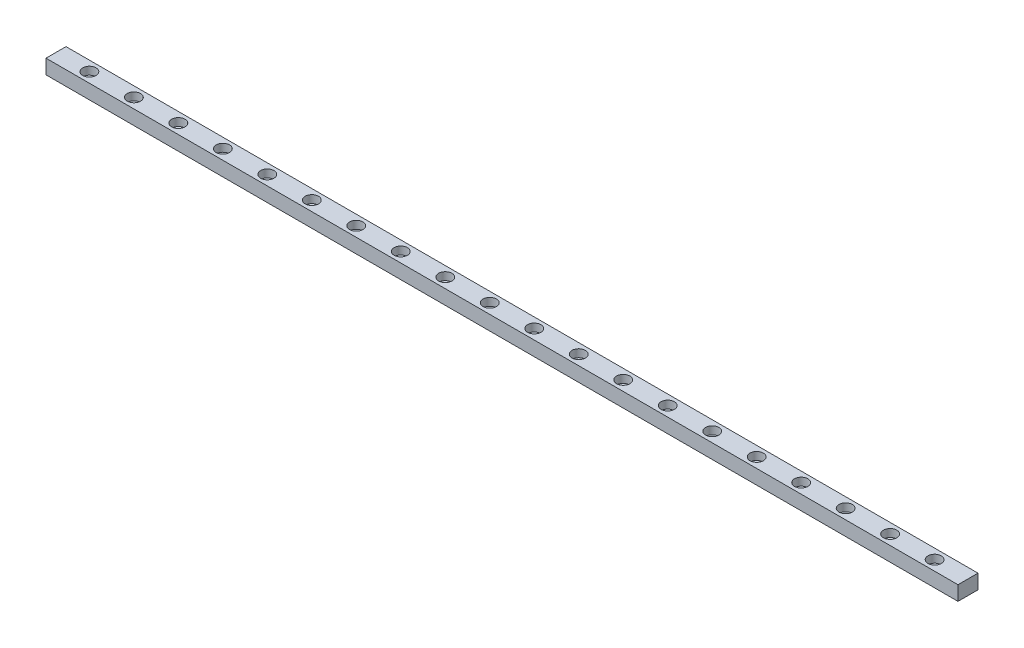
SolidWorks part; units mm, degrees
material "铸造碳钢"
ref_plane "前视基准面" through (0, 0, 0) normal (0, 0, 1) x (1, 0, 0)
ref_plane "上视基准面" through (0, 0, 0) normal (0, 1, 0) x (1, 0, 0)
ref_plane "右视基准面" through (0, 0, 0) normal (1, 0, 0) x (0, 0, -1)
sketch "草图2" plane through (0, 0, 0) normal (1, 0, 0) x (0, 0, -1)
  line L1 (-4.5, 3.25) -> (4.5, 3.25)
  line L2 (-4.5, 3.25) -> (-4.5, -3.25)
  line L3 (-4.5, -3.25) -> (4.5, -3.25)
  line L4 (4.5, 3.25) -> (4.5, -3.25)
  line L5 (-4.5, 3.25) -> (4.5, -3.25) construction
  line L6 (-4.5, -3.25) -> (4.5, 3.25) construction
  point P0 (0, 0)
  dimension "D1" = 9
  dimension "D2" = 6.5
extrude "凸台-拉伸1" add sketch "草图2" along normal blind 410
sketch "草图3" plane through (0, 3.25, 0) normal (0, 1, 0) x (1, 0, 0)
  line L0 (0, 0) -> (410, 0) construction
  line L1 (410, 4.5) -> (410, -4.5) construction
  line L2 (0, 4.5) -> (0, -4.5) construction
  circle A0 centre (15, 0) radius 3
  circle A1 centre (35, 0) radius 3
  circle A2 centre (55, 0) radius 3
  circle A3 centre (75, 0) radius 3
  circle A4 centre (95, 0) radius 3
  circle A5 centre (115, 0) radius 3
  circle A6 centre (135, 0) radius 3
  circle A7 centre (155, 0) radius 3
  circle A8 centre (175, 0) radius 3
  circle A9 centre (195, 0) radius 3
  circle A10 centre (215, 0) radius 3
  circle A11 centre (235, 0) radius 3
  circle A12 centre (255, 0) radius 3
  circle A13 centre (275, 0) radius 3
  circle A14 centre (295, 0) radius 3
  circle A15 centre (315, 0) radius 3
  circle A16 centre (335, 0) radius 3
  circle A17 centre (355, 0) radius 3
  circle A18 centre (375, 0) radius 3
  circle A19 centre (395, 0) radius 3
  dimension "D1" = 15
  dimension "D2" = 6
  dimension "D4" = 20
  dimension "D3" = 20
extrude "切除-拉伸1" cut sketch "草图3" against normal blind 3.5
sketch "草图4" plane through (0, 3.25, 0) normal (0, 1, 0) x (1, 0, 0)
  line L0 (0, 0) -> (90, 0) construction
  line L1 (0, 4.5) -> (0, -4.5) construction
  circle A0 centre (15, 0) radius 1.75
  circle A1 centre (35, 0) radius 1.75
  circle A2 centre (55, 0) radius 1.75
  circle A3 centre (75, 0) radius 1.75
  circle A4 centre (95, 0) radius 1.75
  circle A5 centre (115, 0) radius 1.75
  circle A6 centre (135, 0) radius 1.75
  circle A7 centre (155, 0) radius 1.75
  circle A8 centre (175, 0) radius 1.75
  circle A9 centre (195, 0) radius 1.75
  circle A10 centre (215, 0) radius 1.75
  circle A11 centre (235, 0) radius 1.75
  circle A12 centre (255, 0) radius 1.75
  circle A13 centre (275, 0) radius 1.75
  circle A14 centre (295, 0) radius 1.75
  circle A15 centre (315, 0) radius 1.75
  circle A16 centre (335, 0) radius 1.75
  circle A17 centre (355, 0) radius 1.75
  circle A18 centre (375, 0) radius 1.75
  circle A19 centre (395, 0) radius 1.75
  dimension "D1" = 3.5
  dimension "D3" = 20
  dimension "D2" = 20
extrude "切除-拉伸2" cut sketch "草图4" against normal through all
